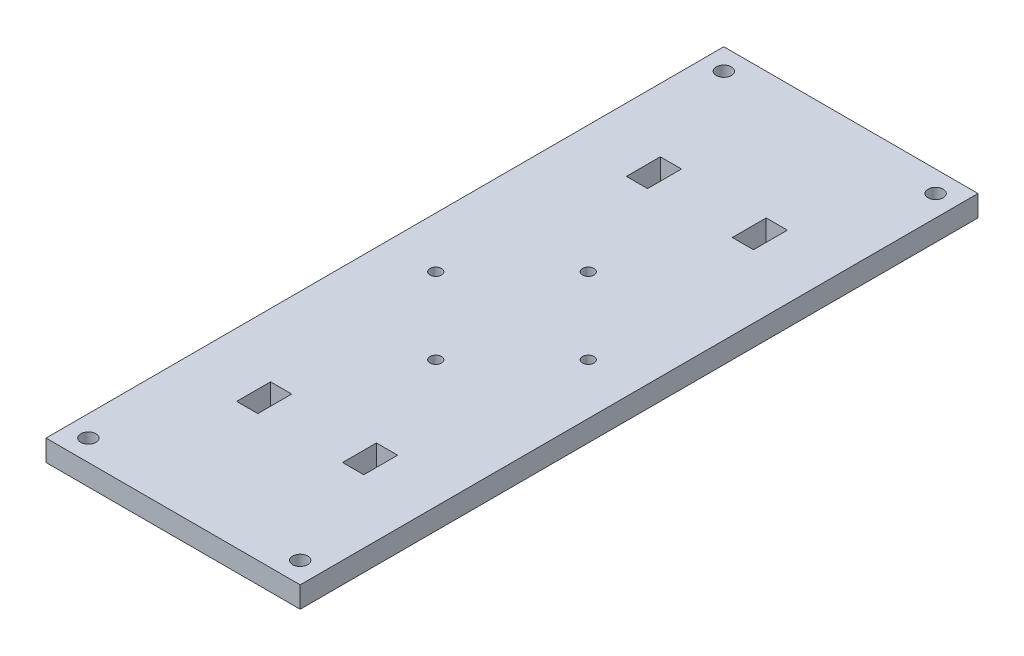
SolidWorks part; units mm, degrees
ref_plane "Front Plane" through (0, 0, 0) normal (0, 0, 1) x (1, 0, 0)
ref_plane "Top Plane" through (0, 0, 0) normal (0, 1, 0) x (1, 0, 0)
ref_plane "Right Plane" through (0, 0, 0) normal (1, 0, 0) x (0, 0, -1)
sketch "Sketch1" plane through (0, 0, 0) normal (0, 1, 0) x (1, 0, 0)
  line L1 (-22.7072, 67.3757) -> (37.2928, 67.3757)
  line L2 (-22.7072, 67.3757) -> (-22.7072, -92.6243)
  line L3 (-22.7072, -92.6243) -> (37.2928, -92.6243)
  line L4 (37.2928, 67.3757) -> (37.2928, -92.6243)
  circle A0 centre (-17.7072, 62.3757) radius 1.78
  circle A1 centre (32.2928, 62.3757) radius 1.78
  circle A2 centre (-17.7072, -87.6243) radius 1.78
  circle A3 centre (32.2928, -87.6243) radius 1.78
  dimension "D1" = 60
  dimension "D2" = 160
  dimension "D4" = 5
  dimension "D5" = 5
  dimension "D7" = 150
  dimension "D8" = 5
  dimension "D9" = 5
  dimension "D10" = 150
extrude "Boss-Extrude1" add sketch "Sketch1" along normal blind 5 contours L1 L4 L3 L2
sketch "Sketch2" plane through (0, 5, 0) normal (0, 1, 0) x (1, 0, 0)
  line L0 (-22.7072, 67.3757) -> (-22.7072, -92.6243) construction
  line L1 (-22.7072, 67.3757) -> (37.2928, 67.3757) construction
  line L2 (37.2928, 67.3757) -> (37.2928, -92.6243) construction
  circle A0 centre (-17.7072, 62.3757) radius 1.78
  circle A1 centre (32.2928, 62.3757) radius 1.78
  circle A2 centre (32.2928, -87.6243) radius 1.78
  circle A3 centre (-17.7072, -87.6243) radius 1.78
  dimension "D1" = 5
  dimension "D2" = 5
  dimension "D3" = 5
  dimension "D4" = 5
  dimension "D5" = 5
  dimension "D6" = 150
extrude "Cut-Extrude1" cut sketch "Sketch2" against normal through all
sketch "Sketch3" plane through (0, 5, 0) normal (0, 1, 0) x (1, 0, 0)
  line L0 (-10.7072, -12.6243) -> (25.2928, -12.6243) construction
  line L1 (-22.7072, 67.3757) -> (-22.7072, -92.6243) construction
  line L2 (-22.7072, 67.3757) -> (37.2928, 67.3757) construction
  circle A0 centre (25.2928, -12.6243) radius 1.35
  circle A1 centre (-10.7072, -12.6243) radius 1.35
  circle A2 centre (7.2928, -12.6243) radius 15.5 construction
  circle A3 centre (7.2928, 5.3757) radius 1.35
  circle A4 centre (7.2928, -30.6243) radius 1.35
  dimension "D1" = 2.7
  dimension "D2" = 31
  dimension "D6" = 18
  dimension "D7" = 18
  dimension "D3" = 36
  dimension "D4" = 30
  dimension "D5" = 80
extrude "Cut-Extrude2" cut sketch "Sketch3" against normal through all
sketch "Sketch4" plane through (0, 5, 0) normal (0, 1, 0) x (1, 0, 0)
  line L0 (37.2928, 67.3757) -> (37.2928, -92.6243) construction
  line L1 (-7.7072, 37.3757) -> (-2.7072, 37.3757)
  line L2 (-7.7072, 37.3757) -> (-7.7072, 29.3757)
  line L3 (-7.7072, 29.3757) -> (-2.7072, 29.3757)
  line L4 (-2.7072, 37.3757) -> (-2.7072, 29.3757)
  line L5 (17.2928, 37.3757) -> (22.2928, 37.3757)
  line L6 (17.2928, 37.3757) -> (17.2928, 29.3757)
  line L7 (17.2928, 29.3757) -> (22.2928, 29.3757)
  line L8 (22.2928, 37.3757) -> (22.2928, 29.3757)
  line L9 (22.2928, -62.6243) -> (17.2928, -62.6243)
  line L10 (22.2928, -62.6243) -> (22.2928, -54.6243)
  line L11 (22.2928, -54.6243) -> (17.2928, -54.6243)
  line L12 (17.2928, -62.6243) -> (17.2928, -54.6243)
  line L13 (-2.7072, -54.6243) -> (-7.7072, -54.6243)
  line L14 (-2.7072, -54.6243) -> (-2.7072, -62.6243)
  line L15 (-2.7072, -62.6243) -> (-7.7072, -62.6243)
  line L16 (-7.7072, -54.6243) -> (-7.7072, -62.6243)
  line L17 (-22.7072, 67.3757) -> (37.2928, 67.3757) construction
  line L18 (-22.7072, -92.6243) -> (37.2928, -92.6243) construction
  line L19 (-22.7072, 67.3757) -> (-22.7072, -92.6243) construction
  dimension "D1" = 30
  dimension "D2" = 30
  dimension "D3" = 30
  dimension "D4" = 30
  dimension "D5" = 15
  dimension "D6" = 5
  dimension "D7" = 15
  dimension "D8" = 5
  dimension "D9" = 8
  dimension "D10" = 8
  dimension "D11" = 5
  dimension "D12" = 15
  dimension "D13" = 5
  dimension "D14" = 8
  dimension "D15" = 15
extrude "Cut-Extrude3" cut sketch "Sketch4" against normal through all
